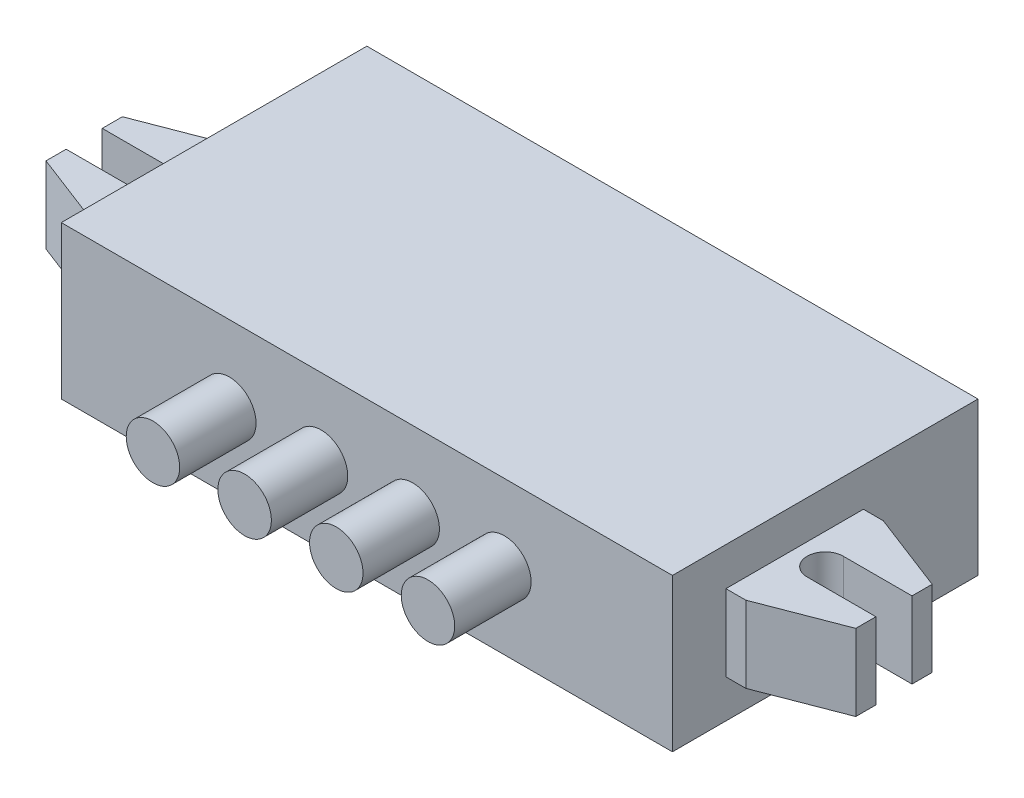
SolidWorks part; units mm, degrees
material "PLA2"
ref_plane "Front Plane" through (0, 0, 0) normal (0, 0, 1) x (1, 0, 0)
ref_plane "Top Plane" through (0, 0, 0) normal (0, 1, 0) x (1, 0, 0)
ref_plane "Right Plane" through (0, 0, 0) normal (1, 0, 0) x (0, 0, -1)
sketch "Sketch1" plane through (0, 0, 0) normal (0, 1, 0) x (1, 0, 0)
  line L1 (-25.4, 12.7) -> (25.4, 12.7)
  line L2 (-25.4, 12.7) -> (-25.4, -12.7)
  line L3 (-25.4, -12.7) -> (25.4, -12.7)
  line L4 (25.4, 12.7) -> (25.4, -12.7)
  line L5 (-25.4, 12.7) -> (25.4, -12.7) construction
  line L6 (-25.4, -12.7) -> (25.4, 12.7) construction
  point P0 (0, 0)
  dimension "D1" = 50.8
  dimension "D2" = 25.4
extrude "Boss-Extrude1" add sketch "Sketch1" along normal mid plane 12.7
sketch "Sketch2" plane through (0, 0, 0) normal (0, 1, 0) x (1, 0, 0)
  line L0 (-25.4, -2.54) -> (25.4, -2.54) construction
  line L1 (-25.4, 12.7) -> (-25.4, -12.7) construction
  line L2 (0, 12.7) -> (0, -12.7) construction
  line L3 (-25.4, 3.175) -> (-27.051, 3.175)
  line L4 (-27.051, 3.175) -> (-33.655, 0.635)
  line L5 (-33.655, 0.635) -> (-33.655, -1.04)
  line L6 (-33.655, -1.04) -> (-27.94, -1.04)
  line L7 (-33.655, -4.04) -> (-27.94, -4.04)
  line L8 (-33.655, -5.715) -> (-33.655, -4.04)
  line L9 (-27.051, -8.255) -> (-33.655, -5.715)
  line L10 (-25.4, -8.255) -> (-27.051, -8.255)
  line L11 (-25.4, 3.175) -> (-25.4, -8.255)
  line L12 (25.4, 12.7) -> (-25.4, 12.7) construction
  line L13 (-25.4, -12.7) -> (25.4, -12.7) construction
  line L14 (25.4, 3.175) -> (25.4, -8.255)
  line L15 (25.4, -8.255) -> (27.051, -8.255)
  line L16 (27.051, -8.255) -> (33.655, -5.715)
  line L17 (33.655, -5.715) -> (33.655, -4.04)
  line L18 (33.655, -4.04) -> (27.94, -4.04)
  line L19 (33.655, -1.04) -> (27.94, -1.04)
  line L20 (33.655, 0.635) -> (33.655, -1.04)
  line L21 (27.051, 3.175) -> (33.655, 0.635)
  line L22 (25.4, 3.175) -> (27.051, 3.175)
  arc A0 (-27.94, -4.04) -> (-27.94, -1.04) centre (-27.94, -2.54) ccw
  arc A1 (27.94, -4.04) -> (27.94, -1.04) centre (27.94, -2.54) cw
  point P33 (-27.2134, -8.255)
  dimension "D1" = 3
  dimension "D2" = 11.43
  dimension "D3" = 2.54
  dimension "D4" = 6.35
  dimension "D5" = 55.88
  dimension "D6" = 67.31
  dimension "D7" = 1.651
extrude "Boss-Extrude2" add sketch "Sketch2" along normal mid plane 6.35
sketch "Sketch3" plane through (0, 0, 12.7) normal (0, 0, 1) x (1, 0, 0)
  line L0 (-25.4, 0) -> (25.4, 0) construction
  line L1 (-25.4, 3.175) -> (-25.4, -3.175) construction
  line L2 (25.4, 3.175) -> (25.4, -3.175) construction
  line L3 (0, 6.35) -> (0, -6.35) construction
  line L4 (-25.4, 6.35) -> (25.4, 6.35) construction
  line L5 (-25.4, -6.35) -> (25.4, -6.35) construction
  circle A0 centre (-3.81, 0) radius 2.2225
  circle A1 centre (-11.43, 0) radius 2.2225
  circle A2 centre (11.43, 0) radius 2.2225
  circle A3 centre (3.81, 0) radius 2.2225
  dimension "D1" = 4.445
  dimension "D2" = 4.445
  dimension "D3" = 3.81
  dimension "D4" = 7.62
extrude "Boss-Extrude3" add sketch "Sketch3" along normal mid plane 12.7
